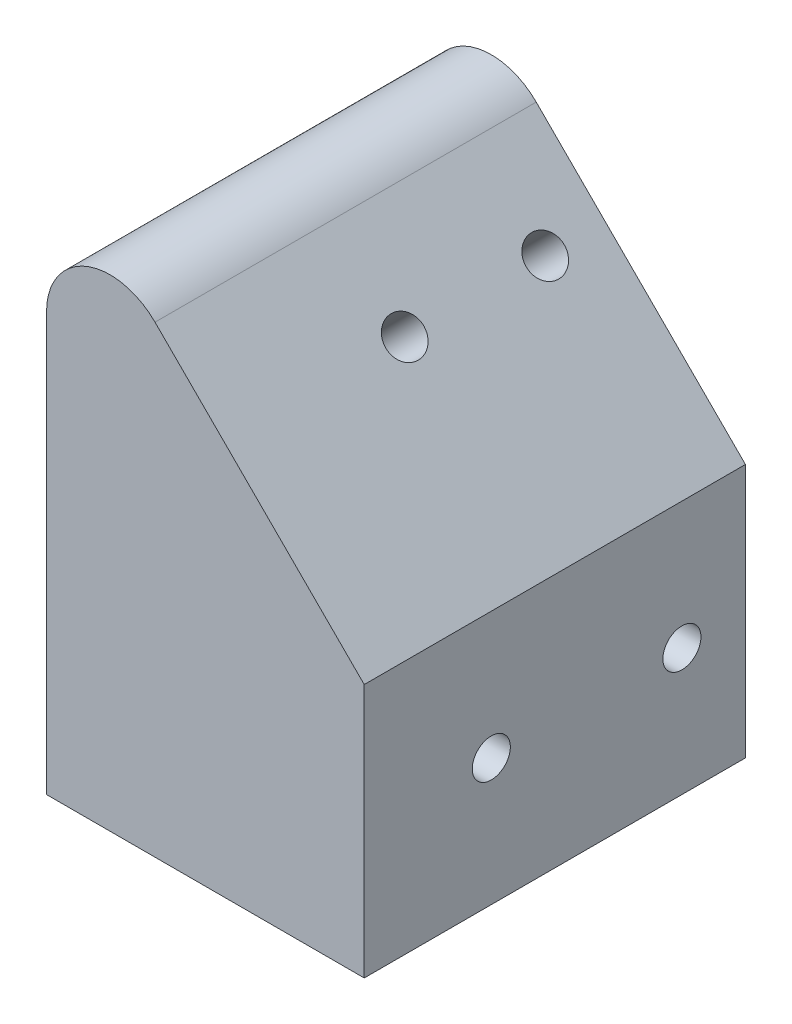
SolidWorks part; units mm, degrees
ref_plane "Alzado" through (0, 0, 0) normal (0, 0, 1) x (1, 0, 0)
ref_plane "Planta" through (0, 0, 0) normal (0, 1, 0) x (1, 0, 0)
ref_plane "Vista lateral" through (0, 0, 0) normal (1, 0, 0) x (0, 0, -1)
sketch "Croquis2" plane through (0, 0, 0) normal (1, 0, 0) x (0, 0, -1)
  line L0 (0, 0) -> (-30, 0)
  line L1 (0, 0) -> (-35.5397, 0) construction
  line L3 (0, -20) -> (-30, -20)
  line L7 (0, -20) -> (0, 0)
  line L8 (-30, -20) -> (-30, 0)
  line L10 (-35.5397, 0) -> (-75.7248, -24.1111) construction
  line L11 (-30, -20) -> (-55.7248, -35.4349) construction
  line L12 (-55.7248, -35.4349) -> (-55.7248, -45.4349) construction
  line L13 (-75.7248, -24.1111) -> (-75.7248, -45.4349) construction
  dimension "D1" = 30
  dimension "D4" = 20
extrude "Saliente-Extruir2" add sketch "Croquis2" along normal blind 25
sketch "Croquis3" plane through (0, 0, 0) normal (0, 0, -1) x (-1, 0, 0)
  line L0 (0, 0) -> (0, 25)
  line L1 (0, 25) -> (-25, 0)
  line L2 (-25, 0) -> (0, 0)
  dimension "D1" = 45
extrude "Saliente-Extruir3" add sketch "Croquis3" against normal through all
fillet "Redondeo1" radius 5 1 edges at (0, 25, 15)
sketch "Croquis8" plane through (0, 0, 0) normal (-1, 0, 0) x (0, 0, 1)
  circle A0 centre (20, -10) radius 1.5
  circle A1 centre (5, -10) radius 1.5
extrude "Cortar-Extruir5" cut sketch "Croquis8" against normal through all
sketch "Croquis9" plane through (12.5, 12.5, 0) normal (0.7071, 0.7071, 0) x (0, 0, -1)
  circle A0 centre (-15.7631, -2.0501) radius 1.5
  circle A1 centre (-4.7071, -2.0501) radius 1.5
extrude "Cortar-Extruir6" cut sketch "Croquis9" against normal through all
move or copy body "Sólido-Mover/Copiar1" [suppressed] bodies to move or copy 113
